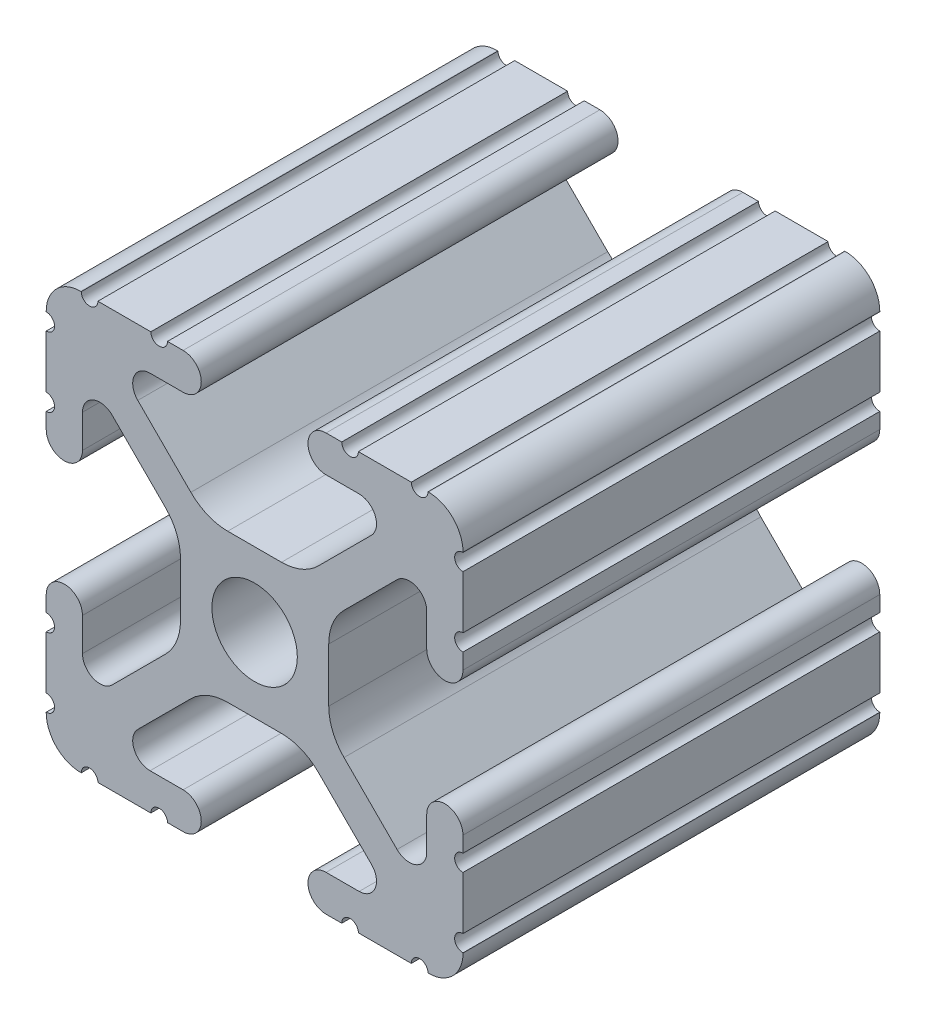
SolidWorks part; units mm, degrees
material "6105-T5 Aluminum"
ref_plane "Front Plane" through (0, 0, 0) normal (0, 0, 1) x (1, 0, 0)
ref_plane "Top Plane" through (0, 0, 0) normal (0, 1, 0) x (1, 0, 0)
ref_plane "Right Plane" through (0, 0, 0) normal (1, 0, 0) x (0, 0, -1)
sketch "Sketch1" plane through (0, 0, 0) normal (0, 0, 1) x (1, 0, 0)
  line L0 (10.5918, 12.7) -> (10.5664, 12.7)
  line L1 (9.5504, 12.7) -> (6.3246, 12.7)
  line L2 (5.3086, 12.7) -> (4.3561, 12.7)
  line L3 (4.3561, 10.4902) -> (6.3701, 10.4902)
  line L4 (7.1192, 8.6817) -> (3.8846, 5.4471)
  line L5 (1.6396, 4.5172) -> (-1.6396, 4.5172)
  line L6 (-3.8846, 5.4471) -> (-7.1192, 8.6817)
  line L7 (-6.3701, 10.4902) -> (-4.3561, 10.4902)
  line L8 (-4.3561, 12.7) -> (-5.3086, 12.7)
  line L9 (-6.3246, 12.7) -> (-9.5504, 12.7)
  line L10 (-10.5664, 12.7) -> (-10.5918, 12.7)
  line L11 (-12.7, 10.5918) -> (-12.7, 10.5664)
  line L12 (-12.7, 9.5504) -> (-12.7, 6.3246)
  line L13 (-12.7, 5.3086) -> (-12.7, 4.3561)
  line L14 (-10.4902, 4.3561) -> (-10.4902, 6.3701)
  line L15 (-8.6817, 7.1192) -> (-5.4471, 3.8846)
  line L16 (-4.5172, 1.6396) -> (-4.5172, -1.6396)
  line L17 (-5.4471, -3.8846) -> (-8.6817, -7.1192)
  line L18 (-10.4902, -6.3701) -> (-10.4902, -4.3561)
  line L19 (-12.7, -4.3561) -> (-12.7, -5.3086)
  line L20 (-12.7, -6.3246) -> (-12.7, -9.5504)
  line L21 (-12.7, -10.5664) -> (-12.7, -10.5918)
  line L22 (-10.5918, -12.7) -> (-10.5664, -12.7)
  line L23 (-9.5504, -12.7) -> (-6.3246, -12.7)
  line L24 (-5.3086, -12.7) -> (-4.3561, -12.7)
  line L25 (-4.3561, -10.4902) -> (-6.3701, -10.4902)
  line L26 (-7.1192, -8.6817) -> (-3.8846, -5.4471)
  line L27 (-1.6396, -4.5172) -> (1.6396, -4.5172)
  line L28 (3.8846, -5.4471) -> (7.1192, -8.6817)
  line L29 (6.3701, -10.4902) -> (4.3561, -10.4902)
  line L30 (4.3561, -12.7) -> (5.3086, -12.7)
  line L31 (6.3246, -12.7) -> (9.5504, -12.7)
  line L32 (10.5664, -12.7) -> (10.5918, -12.7)
  line L33 (12.7, -10.5918) -> (12.7, -10.5664)
  line L34 (12.7, -9.5504) -> (12.7, -6.3246)
  line L35 (12.7, -5.3086) -> (12.7, -4.3561)
  line L36 (10.4902, -4.3561) -> (10.4902, -6.3701)
  line L37 (8.6817, -7.1192) -> (5.4471, -3.8846)
  line L38 (4.5172, -1.6396) -> (4.5172, 1.6396)
  line L39 (5.4471, 3.8846) -> (8.6817, 7.1192)
  line L40 (10.4902, 6.3701) -> (10.4902, 4.3561)
  line L41 (12.7, 4.3561) -> (12.7, 5.3086)
  line L42 (12.7, 6.3246) -> (12.7, 9.5504)
  line L43 (12.7, 10.5664) -> (12.7, 10.5918)
  circle A0 centre (0, 0) radius 2.6035
  arc A1 (12.7, 10.5918) -> (10.5918, 12.7) centre (10.5918, 10.5918) ccw
  arc A2 (9.5504, 12.7) -> (10.5664, 12.7) centre (10.0584, 12.7) ccw
  arc A3 (5.3086, 12.7) -> (6.3246, 12.7) centre (5.8166, 12.7) ccw
  arc A4 (4.3561, 12.7) -> (4.3561, 10.4902) centre (4.3561, 11.5951) ccw
  arc A5 (7.1192, 8.6817) -> (6.3701, 10.4902) centre (6.3701, 9.4308) ccw
  arc A6 (1.6396, 4.5172) -> (3.8846, 5.4471) centre (1.6396, 7.6922) ccw
  arc A7 (-3.8846, 5.4471) -> (-1.6396, 4.5172) centre (-1.6396, 7.6922) ccw
  arc A8 (-6.3701, 10.4902) -> (-7.1192, 8.6817) centre (-6.3701, 9.4308) ccw
  arc A9 (-4.3561, 10.4902) -> (-4.3561, 12.7) centre (-4.3561, 11.5951) ccw
  arc A10 (-6.3246, 12.7) -> (-5.3086, 12.7) centre (-5.8166, 12.7) ccw
  arc A11 (-10.5664, 12.7) -> (-9.5504, 12.7) centre (-10.0584, 12.7) ccw
  arc A12 (-10.5918, 12.7) -> (-12.7, 10.5918) centre (-10.5918, 10.5918) ccw
  arc A13 (-12.7, 9.5504) -> (-12.7, 10.5664) centre (-12.7, 10.0584) ccw
  arc A14 (-12.7, 5.3086) -> (-12.7, 6.3246) centre (-12.7, 5.8166) ccw
  arc A15 (-12.7, 4.3561) -> (-10.4902, 4.3561) centre (-11.5951, 4.3561) ccw
  arc A16 (-8.6817, 7.1192) -> (-10.4902, 6.3701) centre (-9.4308, 6.3701) ccw
  arc A17 (-4.5172, 1.6396) -> (-5.4471, 3.8846) centre (-7.6922, 1.6396) ccw
  arc A18 (-5.4471, -3.8846) -> (-4.5172, -1.6396) centre (-7.6922, -1.6396) ccw
  arc A19 (-10.4902, -6.3701) -> (-8.6817, -7.1192) centre (-9.4308, -6.3701) ccw
  arc A20 (-10.4902, -4.3561) -> (-12.7, -4.3561) centre (-11.5951, -4.3561) ccw
  arc A21 (-12.7, -6.3246) -> (-12.7, -5.3086) centre (-12.7, -5.8166) ccw
  arc A22 (-12.7, -10.5664) -> (-12.7, -9.5504) centre (-12.7, -10.0584) ccw
  arc A23 (-12.7, -10.5918) -> (-10.5918, -12.7) centre (-10.5918, -10.5918) ccw
  arc A24 (-9.5504, -12.7) -> (-10.5664, -12.7) centre (-10.0584, -12.7) ccw
  arc A25 (-5.3086, -12.7) -> (-6.3246, -12.7) centre (-5.8166, -12.7) ccw
  arc A26 (-4.3561, -12.7) -> (-4.3561, -10.4902) centre (-4.3561, -11.5951) ccw
  arc A27 (-7.1192, -8.6817) -> (-6.3701, -10.4902) centre (-6.3701, -9.4308) ccw
  arc A28 (-1.6396, -4.5172) -> (-3.8846, -5.4471) centre (-1.6396, -7.6922) ccw
  arc A29 (3.8846, -5.4471) -> (1.6396, -4.5172) centre (1.6396, -7.6922) ccw
  arc A30 (6.3701, -10.4902) -> (7.1192, -8.6817) centre (6.3701, -9.4308) ccw
  arc A31 (4.3561, -10.4902) -> (4.3561, -12.7) centre (4.3561, -11.5951) ccw
  arc A32 (6.3246, -12.7) -> (5.3086, -12.7) centre (5.8166, -12.7) ccw
  arc A33 (10.5664, -12.7) -> (9.5504, -12.7) centre (10.0584, -12.7) ccw
  arc A34 (10.5918, -12.7) -> (12.7, -10.5918) centre (10.5918, -10.5918) ccw
  arc A35 (12.7, -9.5504) -> (12.7, -10.5664) centre (12.7, -10.0584) ccw
  arc A36 (12.7, -5.3086) -> (12.7, -6.3246) centre (12.7, -5.8166) ccw
  arc A37 (12.7, -4.3561) -> (10.4902, -4.3561) centre (11.5951, -4.3561) ccw
  arc A38 (8.6817, -7.1192) -> (10.4902, -6.3701) centre (9.4308, -6.3701) ccw
  arc A39 (4.5172, -1.6396) -> (5.4471, -3.8846) centre (7.6922, -1.6396) ccw
  arc A40 (5.4471, 3.8846) -> (4.5172, 1.6396) centre (7.6922, 1.6396) ccw
  arc A41 (10.4902, 6.3701) -> (8.6817, 7.1192) centre (9.4308, 6.3701) ccw
  arc A42 (10.4902, 4.3561) -> (12.7, 4.3561) centre (11.5951, 4.3561) ccw
  arc A43 (12.7, 6.3246) -> (12.7, 5.3086) centre (12.7, 5.8166) ccw
  arc A44 (12.7, 10.5664) -> (12.7, 9.5504) centre (12.7, 10.0584) ccw
extrude "Extrude1" add sketch "Sketch1" against normal blind 25.4
